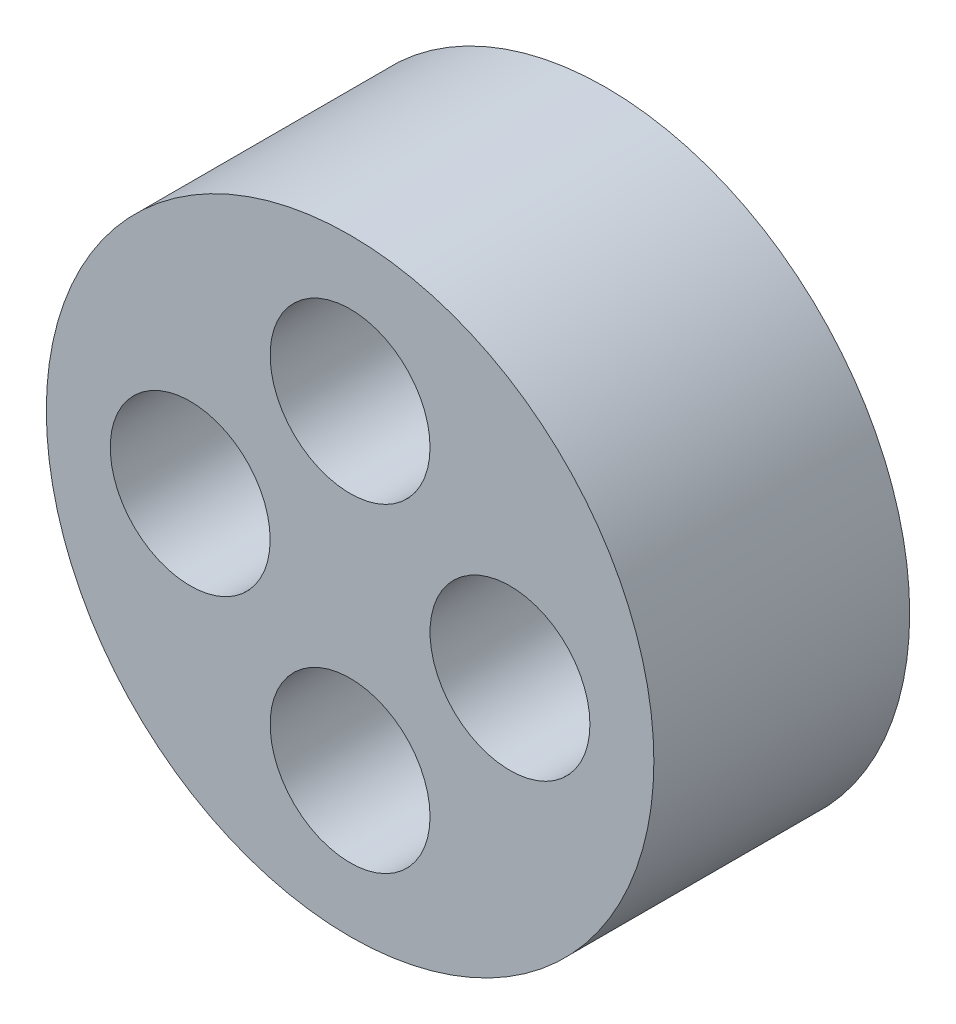
SolidWorks part; units mm, degrees
ref_plane "Alzado" through (0, 0, 0) normal (0, 0, 1) x (1, 0, 0)
ref_plane "Planta" through (0, 0, 0) normal (0, 1, 0) x (1, 0, 0)
ref_plane "Vista lateral" through (0, 0, 0) normal (1, 0, 0) x (0, 0, -1)
sketch "Croquis1" plane through (0, 0, 0) normal (0, 0, 1) x (1, 0, 0)
  circle A0 centre (0, 0) radius 4.75
  arc A1 (-1.2103, 2.1875) -> (1.2103, 2.1875) centre (0, 0) ccw
  circle A2 centre (0, 2.5) radius 1.25
  circle A3 centre (2.5, 0) radius 1.25
  circle A4 centre (0, -2.5) radius 1.25
  circle A5 centre (-2.5, 0) radius 1.25
  dimension "D1" = 9.5
  dimension "D2" = 5
  dimension "D3" = 2.5
  dimension "D4" = 4
extrude "Saliente-Extruir1" add sketch "Croquis1" along normal blind 4 contours A0 A5 A1 A2 A3 A4 | A5 A1 A4 A3 A2
sketch "Croquis2" plane through (0, 0, 4) normal (0, 0, 1) x (1, 0, 0)
  circle A0 centre (0, 0) radius 2.15
  point P3 (0, 0)
  dimension "D1" = 4.3
sketch "Croquis3" plane through (0, 0, 4) normal (0, 0, 1) x (1, 0, 0)
  circle A0 centre (0, 0) radius 2.25
  dimension "D1" = 4.5
